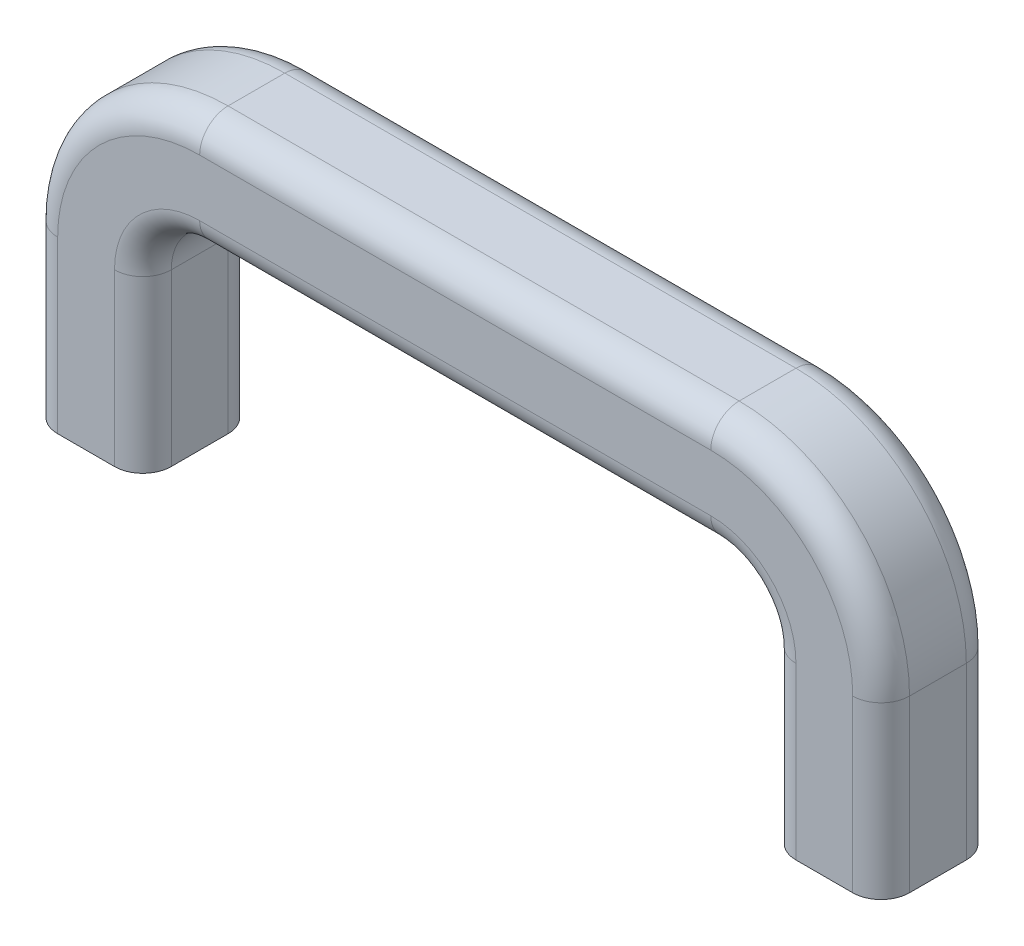
SolidWorks part; units mm, degrees
ref_plane "Přední rovina" through (0, 0, 0) normal (0, 0, 1) x (1, 0, 0)
ref_plane "Horní rovina" through (0, 0, 0) normal (0, 1, 0) x (1, 0, 0)
ref_plane "Pravá rovina" through (0, 0, 0) normal (1, 0, 0) x (0, 0, -1)
sketch "Skica1" plane through (0, 0, 0) normal (0, 1, 0) x (1, 0, 0)
  line L1 (75, -10) -> (-75, -10)
  line L2 (75, -10) -> (75, 10)
  line L3 (75, 10) -> (-75, 10)
  line L4 (-75, -10) -> (-75, 10)
  line L5 (75, -10) -> (-75, 10) construction
  line L6 (75, 10) -> (-75, -10) construction
  point P0 (0, 0)
  dimension "D1" = 150
  dimension "D2" = 20
extrude "Přidat vysunutím1" add sketch "Skica1" along normal blind 60
sketch "Skica2" plane through (0, 0, 10) normal (0, 0, 1) x (1, 0, 0)
  line L0 (-75, 0) -> (75, 0) construction
  line L1 (-55, 0) -> (55, 0)
  line L2 (-55, 0) -> (-55, 40)
  line L3 (-55, 40) -> (55, 40)
  line L4 (55, 0) -> (55, 40)
  line L5 (-75, 60) -> (-75, 0) construction
  line L6 (75, 60) -> (75, 0) construction
  line L7 (-75, 60) -> (75, 60) construction
  dimension "D1" = 20
  dimension "D2" = 20
  dimension "D3" = 20
extrude "Odebrat vysunutím1" cut sketch "Skica2" against normal blind 60
fillet "Zaoblit1" radius 10 2 edges at (55, 40, 0) (-55, 40, 0)
fillet "Zaoblit2" radius 30 2 edges at (75, 60, 0) (-75, 60, 0)
fillet "Zaoblit3" radius 5 20 edges at (55, 15, -10) (52.0711, 37.0711, -10) (-55, 15, -10) (-52.0711, 37.0711, -10) (55, 15, 10) (52.0711, 37.0711, 10) (-55, 15, 10) (-52.0711, 37.0711, 10) (75, 15, -10) (66.2132, 51.2132, -10) (-75, 15, -10) (-66.2132, 51.2132, -10) (-75, 15, 10) (-66.2132, 51.2132, 10) (75, 15, 10) (66.2132, 51.2132, 10) (0, 40, -10) (0, 40, 10) (0, 60, -10) (0, 60, 10)
